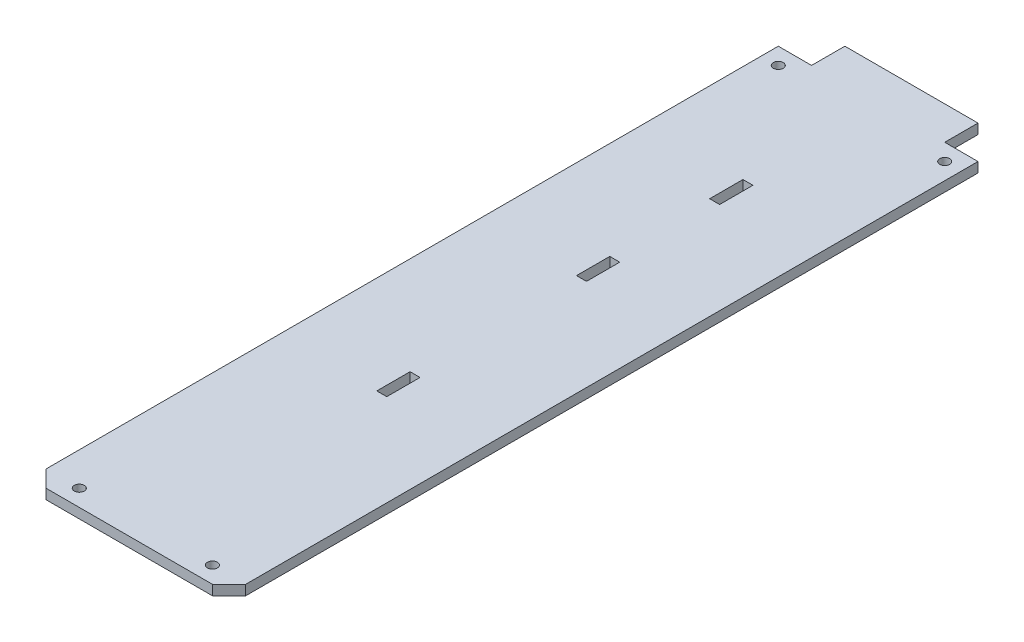
SolidWorks part; units mm, degrees
ref_plane "Front Plane" through (0, 0, 0) normal (0, 0, 1) x (1, 0, 0)
ref_plane "Top Plane" through (0, 0, 0) normal (0, 1, 0) x (1, 0, 0)
ref_plane "Right Plane" through (0, 0, 0) normal (1, 0, 0) x (0, 0, -1)
sketch "Sketch1" plane through (0, 0, 0) normal (0, 1, 0) x (1, 0, 0)
  line L0 (19.1206, 112.5) -> (29.1206, 112.5)
  line L1 (-30.8794, 112.5) -> (-20.8794, 112.5)
  line L2 (-30.8794, 112.5) -> (-30.8794, -112.5)
  line L3 (-30.8794, -112.5) -> (29.1206, -112.5)
  line L4 (29.1206, 112.5) -> (29.1206, -112.5)
  line L8 (-20.8794, 112.5) -> (-20.8794, 122.5)
  line L9 (-20.8794, 122.5) -> (19.1206, 122.5)
  line L10 (19.1206, 112.5) -> (19.1206, 122.5)
  dimension "D1" = 225
  dimension "D2" = 60
  dimension "D3" = 10
  dimension "D4" = 40
  dimension "D5" = 10
extrude "Boss-Extrude1" add sketch "Sketch1" along normal blind 3
sketch "Sketch2" plane through (0, 3, 0) normal (0, 1, 0) x (1, 0, 0)
  line L0 (-20.8794, 112.5) -> (-30.8794, 112.5) construction
  line L1 (19.1206, 122.5) -> (-20.8794, 122.5) construction
  line L2 (-30.8794, 112.5) -> (-30.8794, -112.5) construction
  line L3 (29.1206, 112.5) -> (19.1206, 112.5) construction
  line L4 (29.1206, -112.5) -> (29.1206, 112.5) construction
  line L5 (-30.8794, -112.5) -> (29.1206, -112.5) construction
  line L6 (-1.5, 72.5) -> (1.5, 72.5)
  line L7 (-1.5, 72.5) -> (-1.5, 62.5)
  line L8 (-1.5, 62.5) -> (1.5, 62.5)
  line L9 (1.5, 72.5) -> (1.5, 62.5)
  line L10 (-1.5, 72.5) -> (1.5, 62.5) construction
  line L11 (-1.5, 62.5) -> (1.5, 72.5) construction
  line L12 (-1.5, -27.5) -> (1.5, -27.5)
  line L13 (-1.5, -27.5) -> (-1.5, -37.5)
  line L14 (-1.5, -37.5) -> (1.5, -37.5)
  line L15 (1.5, -27.5) -> (1.5, -37.5)
  line L16 (-1.5, -27.5) -> (1.5, -37.5) construction
  line L17 (-1.5, -37.5) -> (1.5, -27.5) construction
  line L18 (-1.5, 32.5) -> (1.5, 32.5)
  line L19 (-1.5, 32.5) -> (-1.5, 22.5)
  line L20 (-1.5, 22.5) -> (1.5, 22.5)
  line L21 (1.5, 32.5) -> (1.5, 22.5)
  line L22 (-1.5, 32.5) -> (1.5, 22.5) construction
  line L23 (-1.5, 22.5) -> (1.5, 32.5) construction
  circle A0 centre (24.1206, 107.5) radius 1.5
  circle A1 centre (-25.8794, 107.5) radius 1.5
  circle A2 centre (-20.8794, -107.5) radius 1.5
  circle A3 centre (19.1206, -107.5) radius 1.5
  point P16 (0, 67.5)
  point P23 (0, -32.5)
  point P28 (0, 27.5)
  point P35 (0, 62.5)
  dimension "D5" = 3
  dimension "D6" = 3
  dimension "D7" = 3
  dimension "D8" = 3
  dimension "D1" = 5
  dimension "D2" = 5
  dimension "D3" = 5
  dimension "D4" = 5
  dimension "D9" = 10
  dimension "D10" = 5
  dimension "D11" = 5
  dimension "D12" = 10
  dimension "D13" = 10
  dimension "D14" = 10
  dimension "D15" = 3
  dimension "D16" = 3
  dimension "D17" = 3
  dimension "D18" = 50
  dimension "D19" = 30
  dimension "D20" = 50
  dimension "D21" = 10
extrude "Cut-Extrude1" cut sketch "Sketch2" against normal blind 25
chamfer "Chamfer1" distance 5 angle 45 2 edges at (-30.8794, 1.5, 112.5) (29.1206, 1.5, 112.5)
